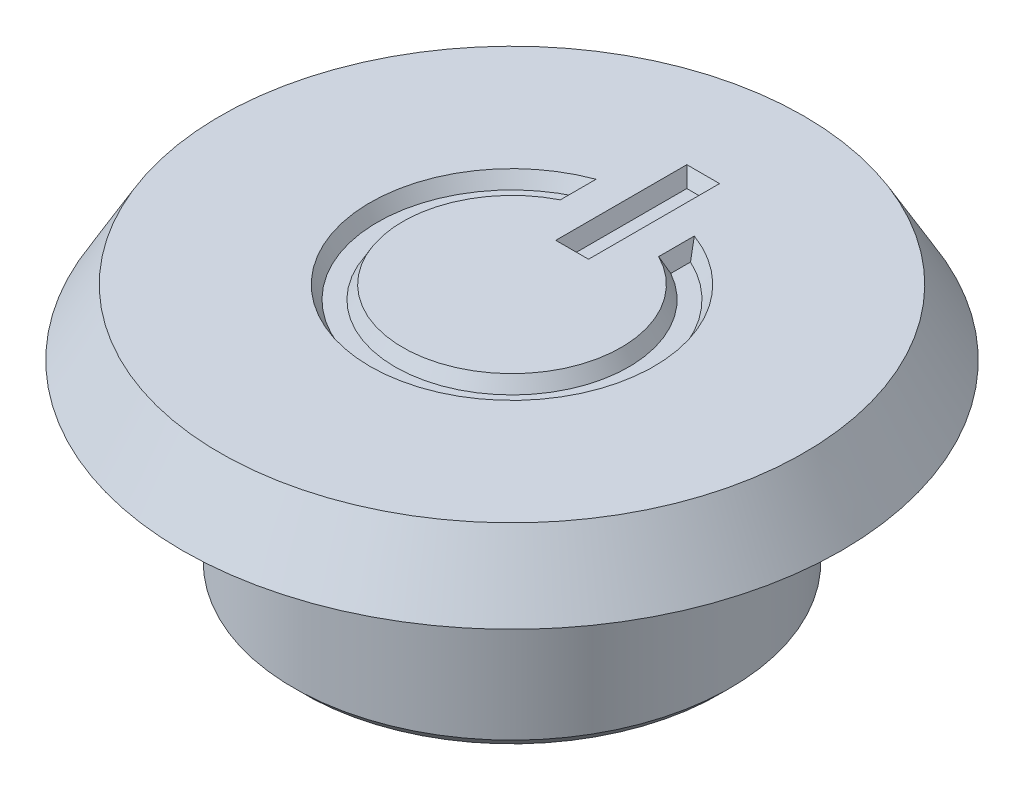
SolidWorks part; units mm, degrees
ref_plane "Спереди" through (0, 0, 0) normal (0, 0, 1) x (1, 0, 0)
ref_plane "Сверху" through (0, 0, 0) normal (0, 1, 0) x (1, 0, 0)
ref_plane "Справа" through (0, 0, 0) normal (1, 0, 0) x (0, 0, -1)
sketch "Эскиз1" plane through (0, 0, 0) normal (0, 0, 1) x (1, 0, 0)
  line L0 (0, 64.101) -> (-26.7321, 64.101)
  line L2 (-25, 61.101) -> (-20, 61.101)
  line L3 (-20, 61.101) -> (-20, 42.101)
  line L4 (-19, 41.101) -> (-18, 41.101)
  line L5 (-18, 41.101) -> (-18, 58.101)
  line L6 (-15, 61.101) -> (0, 61.101)
  line L7 (0, 61.101) -> (0, 64.101)
  line L8 (-26.7321, 64.101) -> (-30.1962, 58.101)
  line L9 (-30.1962, 58.101) -> (-26.7321, 58.101)
  line L10 (-26.7321, 58.101) -> (-25, 61.101)
  line L11 (-20, 42.101) -> (-19, 41.101)
  arc A0 (-18, 58.101) -> (-15, 61.101) centre (-15, 58.101) cw
  point P2 (-20, 41.101)
  dimension "D10" = 3
  dimension "D2" = 2
  dimension "D3" = 20
  dimension "D4" = 3
  dimension "D5" = 6
  dimension "D6" = 60
  dimension "D7" = 20
  dimension "D8" = 3
  dimension "D9" = 5
revolve "Повернуть1" add sketch "Эскиз1" angle 360 about L7
sketch "Эскиз3" plane through (0, 64.101, 0) normal (0, 1, 0) x (1, 0, 0)
  line L0 (-4.5, 12.1963) -> (-4.5, 8.9303)
  line L1 (-1.5, 17.5096) -> (1.5, 17.5096)
  line L2 (-1.5, 17.5096) -> (-1.5, 5.5096)
  line L3 (-1.5, 5.5096) -> (1.5, 5.5096)
  line L4 (1.5, 17.5096) -> (1.5, 5.5096)
  line L5 (-1.5, 17.5096) -> (1.5, 5.5096) construction
  line L6 (-1.5, 5.5096) -> (1.5, 17.5096) construction
  line L7 (4.5, 12.1963) -> (4.5, 8.9303)
  line L8 (-4.5, 17.5096) -> (-4.5, 5.5096) construction
  line L9 (4.5, 17.5096) -> (4.5, 5.5096) construction
  arc A0 (-4.5, 8.9303) -> (4.5, 8.9303) centre (0, 0) ccw
  arc A1 (-4.5, 12.1963) -> (4.5, 12.1963) centre (0, 0) ccw
  circle A2 centre (0, 0) radius 13 construction
  circle A3 centre (0, 0) radius 10 construction
  point P5 (0, 11.5096)
  dimension "D1" = 3
  dimension "D2" = 3
  dimension "D3" = 12
  dimension "D4" = 3
  dimension "D5" = 3
extrude "Вырез-Вытянуть1" cut sketch "Эскиз3" against normal blind 1.2 draft 30
